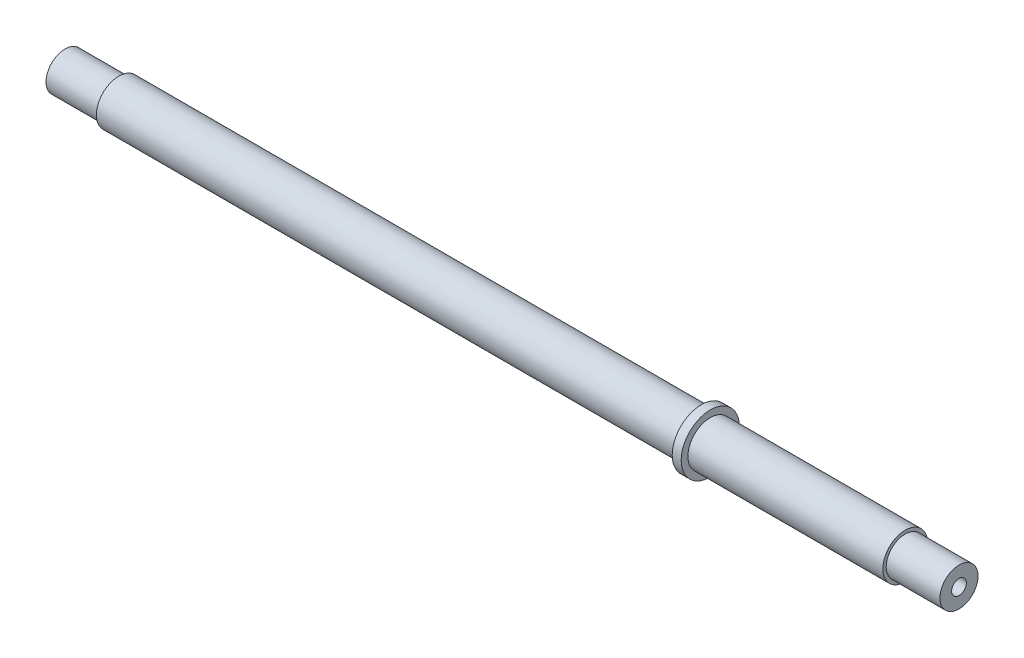
SolidWorks part; units mm, degrees
ref_plane "Front Plane" through (0, 0, 0) normal (0, 0, 1) x (1, 0, 0)
ref_plane "Top Plane" through (0, 0, 0) normal (0, 1, 0) x (1, 0, 0)
ref_plane "Right Plane" through (0, 0, 0) normal (1, 0, 0) x (0, 0, -1)
sketch "Sketch1" plane through (0, 0, 0) normal (0, 1, 0) x (1, 0, 0)
  line L0 (-69.6099, 0) -> (37.6057, 0) construction
sketch "Sketch2" plane through (0, 0, 0) normal (0, 1, 0) x (1, 0, 0)
  line L0 (-99.75, 4.25) -> (-87.75, 4.25)
  line L1 (-87.75, 4.25) -> (-87.75, 5)
  line L2 (-87.75, 5) -> (42.25, 5)
  line L3 (42.25, 5) -> (42.25, 6.5)
  line L4 (42.25, 6.5) -> (44.25, 6.5)
  line L5 (44.25, 6.5) -> (44.25, 5)
  line L6 (44.25, 5) -> (87.75, 5)
  line L7 (87.75, 5) -> (87.75, 4.25)
  line L8 (87.75, 4.25) -> (99.75, 4.25)
  line L9 (99.75, 4.25) -> (99.75, 0)
  line L10 (-200069.6099, 0) -> (200037.6057, 0) construction
  line L11 (99.75, 0) -> (-99.75, 0)
  line L12 (-99.75, 0) -> (-99.75, 4.25)
  dimension "D1" = 12
  dimension "D2" = 2
  dimension "D3" = 1.5
  dimension "D4" = 43.5
  dimension "D5" = 130
  dimension "D6" = 5
  dimension "D7" = 4.25
revolve "Revolve1" add sketch "Sketch2" angle 360 about L0
hole_wizard "M4x0.7 Tapped Hole1" positions "Sketch3" profile "Sketch5" tap size "M4x0.7" standard "ANSI Metric"
sketch "Sketch3" plane through (99.75, 0, 0) normal (1, 0, 0) x (0, 0, -1)
  point P0 (0, 0)
sketch "Sketch5" plane through (99.75, 0, 0) normal (0, 1, 0) x (0, 0, -1)
  line L0 (0, 0) -> (0, 15.9914)
  line L1 (0, 15.9914) -> (1.65, 15)
  line L2 (1.65, 15) -> (1.65, 0)
  line L5 (1.65, 0) -> (0, 0)
  line L10 (0, 15.9914) -> (-1.65, 15) construction
  line L11 (0, -6.35) -> (0, 107.95) construction
  dimension "Tap Drill Dia." = 3.3
  dimension "Tap Drill Depth" = 15
  dimension "Drill Angle" = 118
cosmetic thread "Hole Thread1"
mirror "Mirror1" about plane through (0, 0, 0) normal (1, 0, 0) of "M4x0.7 Tapped Hole1"
cosmetic thread "Hole Thread2"
